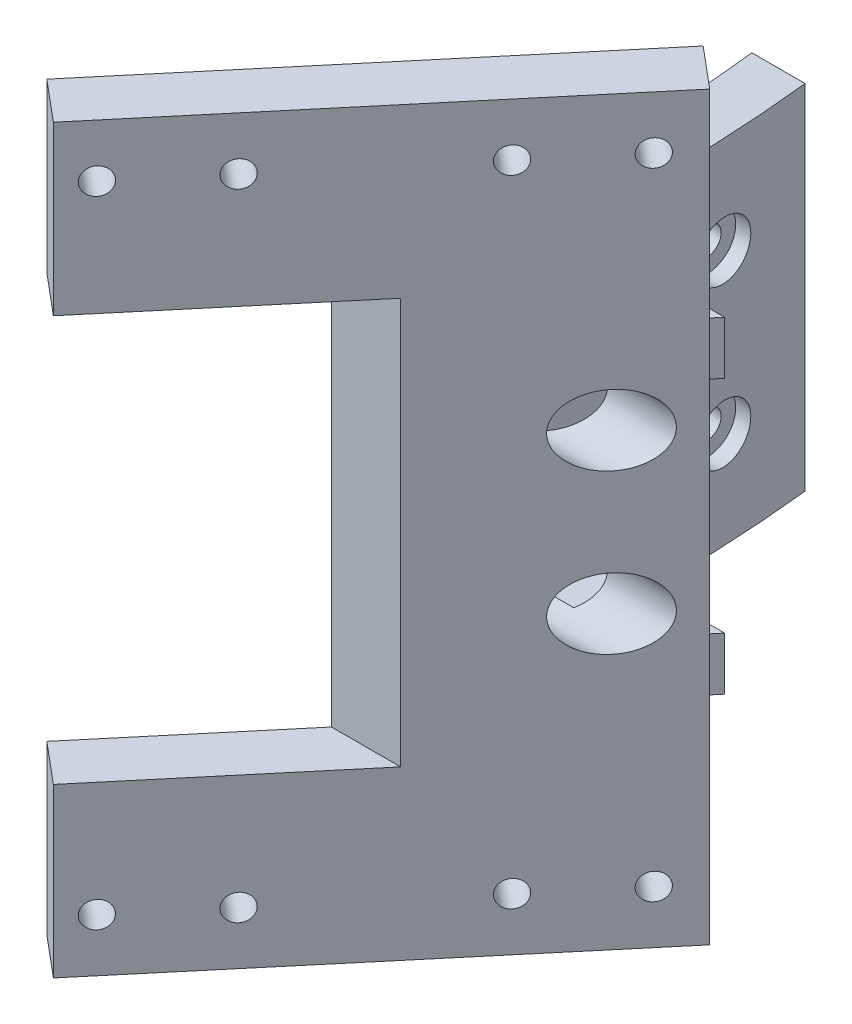
SolidWorks part; units mm, degrees
ref_plane "前视基准面" through (0, 0, 0) normal (0, 0, 1) x (1, 0, 0)
ref_plane "上视基准面" through (0, 0, 0) normal (0, 1, 0) x (1, 0, 0)
ref_plane "右视基准面" through (0, 0, 0) normal (1, 0, 0) x (0, 0, -1)
other "Configuration Table"
sketch3d "3D草图1"
  point P0 (266.2557, 0, 5.9507)
  point P1 (266.2557, 10, 5.9507)
  point P2 (259.8278, 0, 13.6112)
ref_plane "基准面1" through (159.1754, 0, 133.564) normal (0.766, 0, 0.6428) x (0.6428, 0, -0.766)
sketch "草图1" plane through (159.1754, 0, 133.564) normal (0.766, 0, 0.6428) x (0.6428, 0, -0.766)
  line L0 (166.5873, -42) -> (166.5873, 42)
  line L1 (166.5873, 42) -> (113.7873, 42)
  line L2 (113.7873, 42) -> (113.7873, -42)
  line L3 (113.7873, -42) -> (166.5873, -42)
extrude "凸台-拉伸1" add sketch "草图1" against normal blind 6
sketch3d "3D草图2"
  point P0 (266.2557, 0, 5.9507)
  point P1 (266.2557, 10, 5.9507)
  point P2 (259.8278, 0, 13.6112)
ref_plane "基准面2" through (159.1754, 0, 133.564) normal (0.766, 0, 0.6428) x (0.6428, 0, -0.766)
sketch "草图2" plane through (159.1754, 0, 133.564) normal (0.766, 0, 0.6428) x (0.6428, 0, -0.766)
  circle A0 centre (117.2873, -36) radius 1.5
  circle A1 centre (117.2873, 36) radius 1.5
  circle A2 centre (150.6873, 36) radius 1.5
  circle A3 centre (128.6873, 36) radius 1.5
  circle A4 centre (128.6873, -36) radius 1.5
  circle A5 centre (162.0873, 36) radius 1.5
  circle A6 centre (162.0873, -36) radius 1.5
  circle A7 centre (150.6873, -36) radius 1.5
extrude "切除-拉伸1" cut sketch "草图2" against normal blind 8
sketch3d "3D草图3"
  point P0 (0, 0, 25)
  point P1 (10, 0, 25)
  point P2 (0, 10, 25)
ref_plane "基准面3" through (0, 0, 25) normal (0, 0, 1) x (1, 0, 0)
sketch "草图3" plane through (0, 0, 25) normal (0, 0, 1) x (1, 0, 0)
  line L0 (220, -23) -> (280, -23)
  line L1 (280, -23) -> (280, 23)
  line L2 (280, 23) -> (220, 23)
  line L3 (220, 23) -> (220, -23)
extrude "切除-拉伸2" cut sketch "草图3" along normal blind 50
sketch3d "3D草图4"
  point P0 (0, 20, 0)
  point P1 (10, 20, 0)
  point P2 (0, 20, 10)
ref_plane "基准面4" through (0, 20, 0) normal (0, -1, 0) x (-1, 0, 0)
sketch "草图4" plane through (0, 20, 0) normal (0, -1, 0) x (-1, 0, 0)
  line L0 (-249.1238, 22) -> (-243.0866, 22)
  line L1 (-242.0978, -22) -> (-248.1779, -22)
  spline S0 degree 6 poles (-248.1779, -22) (-248.8001, -18.1116) (-249.3071, -14.0548) (-249.6966, -9.8437) (-249.9631, -5.4961) (-250.1, -1.0311) (-250.1, 3.5312) knots 0.698641 0.698641 0.698641 0.698641 0.698641 0.698641 0.698641 1 1 1 1 1 1 1
  spline S1 degree 5 poles (-250.1, 3.5312) (-250.1, 7.3981) (-249.9975, 11.1921) (-249.7978, 14.8992) (-249.5055, 18.5058) (-249.1238, 22) knots 0 0 0 0 0 0 0.212851 0.212851 0.212851 0.212851 0.212851 0.212851
  spline S2 degree 5 poles (-243.0866, 22) (-243.4813, 18.5314) (-243.7849, 14.9338) (-243.993, 11.2231) (-244.1, 7.4164) (-244.1, 3.5312) knots 0.778865 0.778865 0.778865 0.778865 0.778865 0.778865 1 1 1 1 1 1
  spline S3 degree 6 poles (-244.1, 3.5312) (-244.1, -1.0699) (-243.956, -5.5651) (-243.6764, -9.9297) (-243.2689, -14.139) (-242.7411, -18.1695) (-242.0978, -22) knots 0 0 0 0 0 0 0 0.314255 0.314255 0.314255 0.314255 0.314255 0.314255 0.314255
extrude "凸台-拉伸2" add sketch "草图4" along normal blind 40
sketch3d "3D草图5"
  point P0 (0, -18.5, 0)
  point P1 (10, -18.5, 0)
  point P2 (0, -18.5, 10)
ref_plane "基准面5" through (0, -18.5, 0) normal (0, -1, 0) x (-1, 0, 0)
sketch "草图5" plane through (0, -18.5, 0) normal (0, -1, 0) x (-1, 0, 0)
  line L0 (-246, -4) -> (-266, -4)
  line L1 (-266, -4) -> (-250, -23)
  line L2 (-250, -23) -> (-244, -23)
  line L3 (-244, -23) -> (-246, -4)
extrude "凸台-拉伸3" add sketch "草图5" against normal blind 6
sketch3d "3D草图6"
  point P0 (0, 12.5, 0)
  point P1 (10, 12.5, 0)
  point P2 (0, 12.5, 10)
ref_plane "基准面6" through (0, 12.5, 0) normal (0, -1, 0) x (-1, 0, 0)
sketch "草图6" plane through (0, 12.5, 0) normal (0, -1, 0) x (-1, 0, 0)
  line L0 (-246, -4) -> (-266, -4)
  line L1 (-266, -4) -> (-250, -23)
  line L2 (-250, -23) -> (-244, -23)
  line L3 (-244, -23) -> (-246, -4)
extrude "凸台-拉伸4" add sketch "草图6" against normal blind 6
sketch3d "3D草图7"
  point P0 (285, 0, 0)
  point P1 (285, 10, 0)
  point P2 (285, 0, 10)
ref_plane "基准面7" through (285, 0, 0) normal (1, 0, 0) x (0, 0, -1)
sketch "草图7" plane through (285, 0, 0) normal (1, 0, 0) x (0, 0, -1)
  circle A0 centre (12, -9) radius 1.6
  circle A1 centre (-12, -9) radius 1.6
  circle A2 centre (12, 9) radius 1.6
  circle A3 centre (-12, 9) radius 1.6
extrude "切除-拉伸3" cut sketch "草图7" against normal blind 70
sketch3d "3D草图8"
  point P0 (260, 0, 0)
  point P1 (260, 10, 0)
  point P2 (260, 0, 10)
ref_plane "基准面8" through (260, 0, 0) normal (1, 0, 0) x (0, 0, -1)
sketch "草图8" plane through (260, 0, 0) normal (1, 0, 0) x (0, 0, -1)
  circle A0 centre (12, -9) radius 3.25
  circle A1 centre (-12, -9) radius 3.25
  circle A2 centre (12, 9) radius 3.25
  circle A3 centre (-12, 9) radius 3.25
extrude "切除-拉伸4" cut sketch "草图8" against normal blind 12
sketch3d "3D草图9"
  point P0 (275, 0, 0)
  point P1 (275, 10, 0)
  point P2 (275, 0, 10)
ref_plane "基准面9" through (275, 0, 0) normal (1, 0, 0) x (0, 0, -1)
sketch "草图9" plane through (275, 0, 0) normal (1, 0, 0) x (0, 0, -1)
  circle A0 centre (-12, -9) radius 4
  circle A1 centre (-12, 9) radius 4
extrude "切除-拉伸5" cut sketch "草图9" against normal blind 23.5
